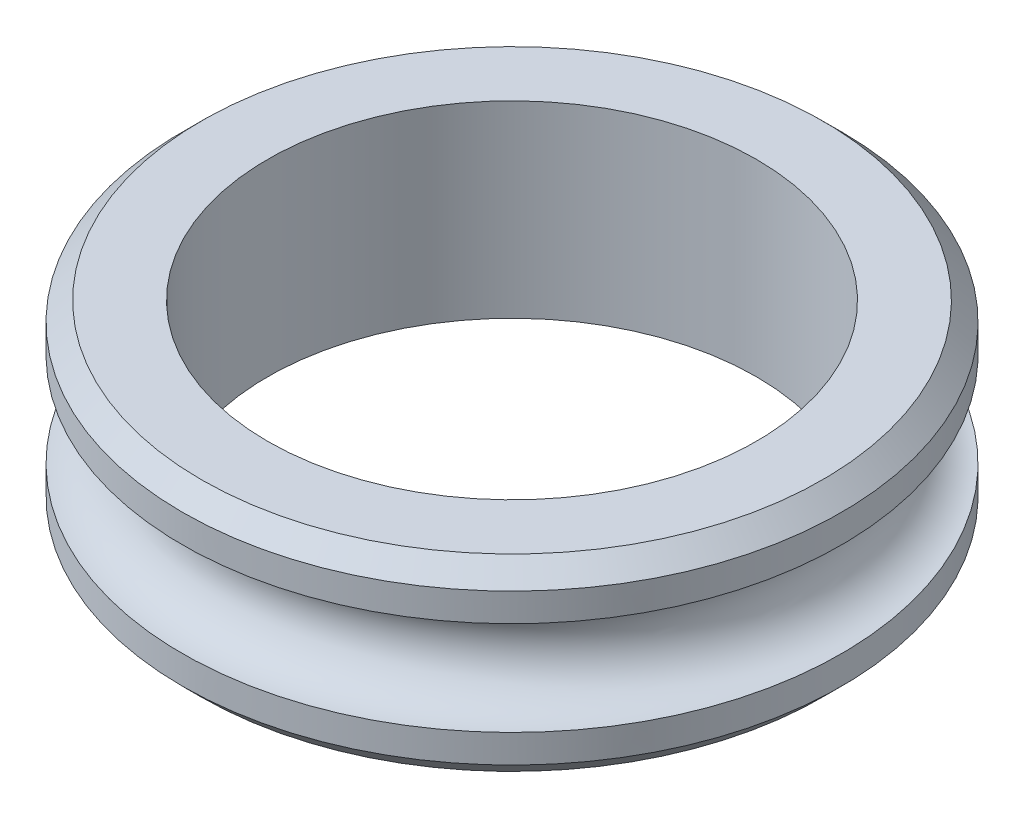
SolidWorks part; units mm, degrees
ref_plane "Front Plane" through (0, 0, 0) normal (0, 0, 1) x (1, 0, 0)
ref_plane "Top Plane" through (0, 0, 0) normal (0, 1, 0) x (1, 0, 0)
ref_plane "Right Plane" through (0, 0, 0) normal (1, 0, 0) x (0, 0, -1)
sketch "Sketch1" plane through (0, 0, 0) normal (0, 1, 0) x (1, 0, 0)
  circle A0 centre (0, 0) radius 12.975
  circle A1 centre (0, 0) radius 17.5
  dimension "D1" = 25.95
  dimension "D2" = 35
extrude "Corpo Externo Ø35×10" add sketch "Sketch1" along normal blind 10 contours A1 A0
chamfer "Chanfros 1×45°" distance 1 angle 45 2 edges at (0, 0, 17.5) (0, 10, 17.5)
sketch "Sketch2" plane through (0, 0, 0) normal (0, 0, 1) x (1, 0, 0)
  line L0 (0, 0) -> (0, 10) construction
  line L1 (16.5, 10) -> (-16.5, 10) construction
  line L2 (17.5, 5) -> (-17.5, 5) construction
  line L3 (17.5, 1) -> (17.5, 9) construction
  line L4 (-17.5, 9) -> (-17.5, 1) construction
  line L6 (-17.5, 7.5) -> (-17.5, 2.5)
  arc A0 (-17.5, 7.5) -> (-17.5, 2.5) centre (-17.5, 5) cw
  dimension "D1" = 2.5
revolve "Canal" cut sketch "Sketch2" angle 360 about L0
